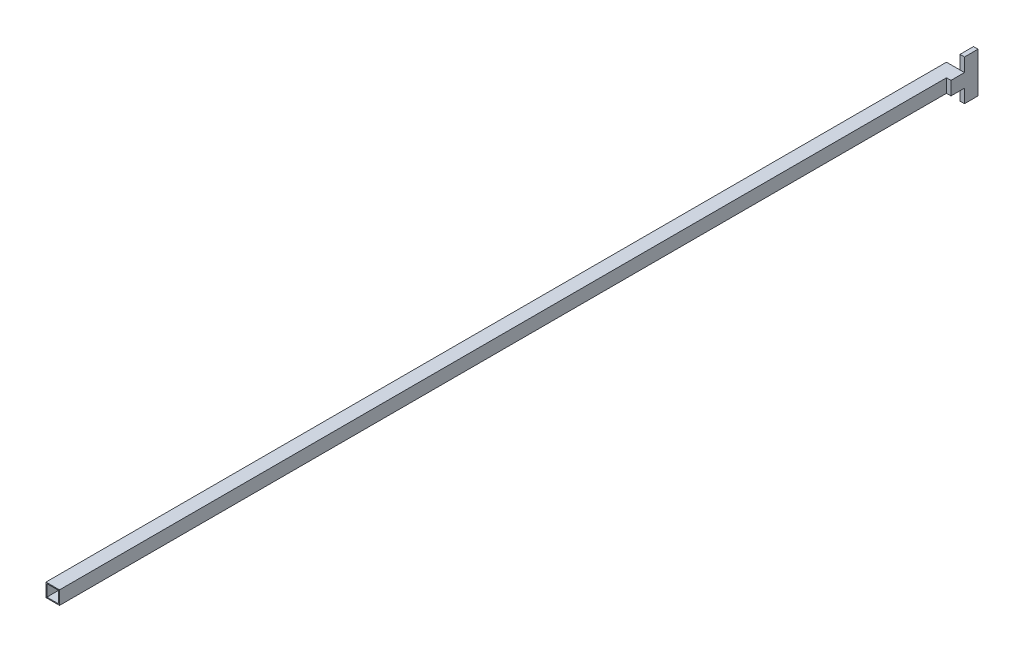
SolidWorks part; units mm, degrees
ref_plane "Front Plane" through (0, 0, 0) normal (0, 0, 1) x (1, 0, 0)
ref_plane "Top Plane" through (0, 0, 0) normal (0, 1, 0) x (1, 0, 0)
ref_plane "Right Plane" through (0, 0, 0) normal (1, 0, 0) x (0, 0, -1)
sketch "Sketch1" plane through (0, 0, 0) normal (0, 0, 1) x (1, 0, 0)
  line L1 (15, 15) -> (-15, 15)
  line L2 (15, 15) -> (15, -15)
  line L3 (15, -15) -> (-15, -15)
  line L4 (-15, 15) -> (-15, -15)
  line L5 (15, 15) -> (-15, -15) construction
  line L6 (15, -15) -> (-15, 15) construction
  line L7 (13, 13) -> (-13, 13)
  line L8 (13, 13) -> (13, -13)
  line L9 (13, -13) -> (-13, -13)
  line L10 (-13, 13) -> (-13, -13)
  line L11 (13, 13) -> (-13, -13) construction
  line L12 (13, -13) -> (-13, 13) construction
  point P0 (0, 0)
  point P6 (0, 0)
  dimension "D1" = 15
  dimension "D2" = 13
  dimension "D3" = 15
extrude "Boss-Extrude1" add sketch "Sketch1" along normal blind 2000
ref_plane "Plane1" through (15, 0, 0) normal (1, 0, 0) x (0, 0, -1)
sketch "Sketch2" plane through (15, 0, 0) normal (1, 0, 0) x (0, 0, -1)
  line L0 (-2000, 15) -> (0, 15) construction
  line L1 (-30, 15) -> (0, 15)
  line L2 (-30, 15) -> (-30, -15)
  line L3 (-30, -15) -> (0, -15)
  line L4 (30, 15) -> (30, -15)
  line L7 (30, 15) -> (30, 45)
  line L8 (30, 45) -> (0, 45)
  line L9 (0, 15) -> (0, 45)
  line L11 (30, -15) -> (30, -45)
  line L12 (30, -45) -> (0, -45)
  line L13 (0, -15) -> (0, -45)
  dimension "D1" = 30
  dimension "D2" = 30
  dimension "D3" = 30
  dimension "D4" = 30
  dimension "D5" = 30
  dimension "D6" = 15
  dimension "D7" = 30
  dimension "D8" = 30
  dimension "D9" = 30
extrude "Boss-Extrude2" add sketch "Sketch2" along normal blind 10 contours L2 L3 L13 L12 L11 L4 L7 L8 L9 L1
